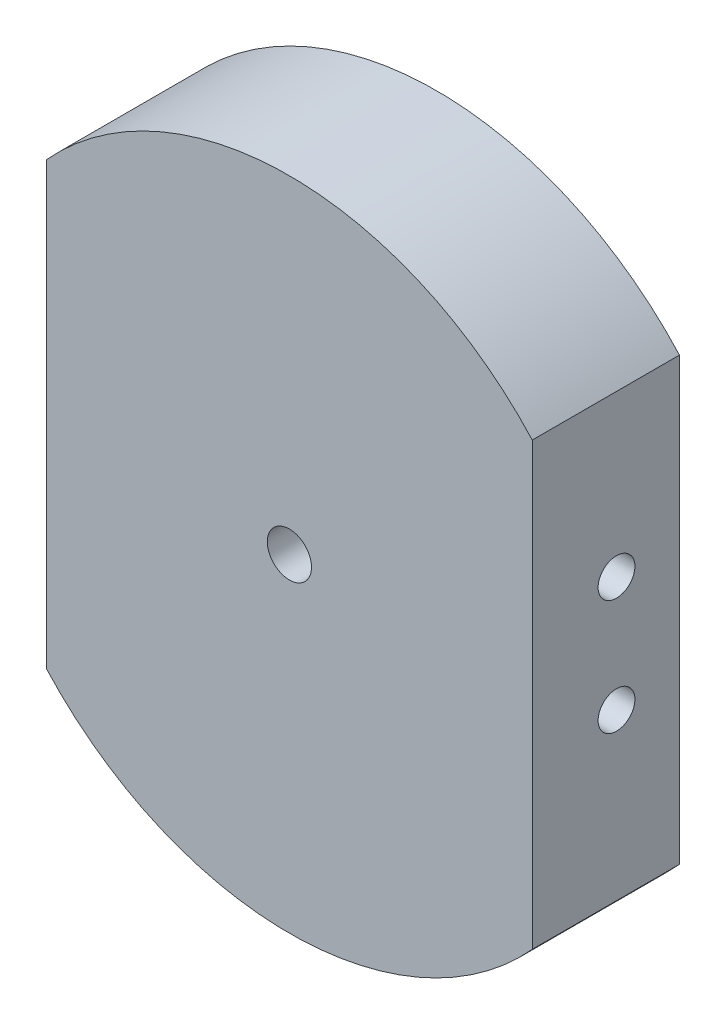
SolidWorks part; units mm, degrees
ref_plane "Front Plane" through (0, 0, 0) normal (0, 0, 1) x (1, 0, 0)
ref_plane "Top Plane" through (0, 0, 0) normal (0, 1, 0) x (1, 0, 0)
ref_plane "Right Plane" through (0, 0, 0) normal (1, 0, 0) x (0, 0, -1)
sketch "Sketch1" plane through (0, 0, 0) normal (0, 0, 1) x (1, 0, 0)
  circle A0 centre (0, 0) radius 55
  circle A1 centre (0, 0) radius 3
extrude "Boss-Extrude1" add sketch "Sketch1" along normal blind 20
sketch "Sketch2" plane through (0, 0, 20) normal (0, 0, 1) x (1, 0, 0)
  line L0 (-55, 0) -> (55, 0) construction
  line L1 (-54.0833, -10) -> (54.0833, -10) construction
  line L2 (-47.962, 14.4195) -> (-41.962, 14.4195) construction
  line L7 (-41.362, 16.6207) -> (-41.362, -16.6207)
  line L8 (0, 0) -> (0, 19.7694) construction
  line L9 (41.362, 16.6207) -> (41.362, -16.6207)
  line L11 (48.562, 0) -> (48.562, -1.9737)
  circle A0 centre (0, 0) radius 55 construction
  circle A1 centre (0, 0) radius 52
  arc A2 (-41.362, -16.6207) -> (41.362, -16.6207) centre (0, 0) ccw
  arc A7 (-41.362, 16.6207) -> (41.362, 16.6207) centre (0, 0) cw
  dimension "D3" = 10
extrude "Cut-Extrude1" cut sketch "Sketch2" against normal blind 10
sketch "Sketch3" plane through (0, 0, 20) normal (0, 0, 1) x (1, 0, 0)
  line L2 (-41.362, 16.6207) -> (-41.362, -16.6207)
  line L3 (41.362, -16.6207) -> (41.362, 16.6207)
  line L4 (-41.362, 16.6207) -> (-41.362, -16.6207)
  line L5 (41.362, -16.6207) -> (41.362, 16.6207)
  circle A0 centre (0, 0) radius 73.6451
  arc A2 (41.362, 16.6207) -> (-41.362, 16.6207) centre (0, 0) ccw
  arc A3 (-41.362, -16.6207) -> (41.362, -16.6207) centre (0, 0) ccw
  arc A4 (41.362, 16.6207) -> (-41.362, 16.6207) centre (0, 0) ccw
  arc A5 (-41.362, -16.6207) -> (41.362, -16.6207) centre (0, 0) ccw
  dimension "D1" = 0
extrude "Cut-Extrude2" cut sketch "Sketch3" against normal blind 40
sketch "Sketch6" plane through (0, 0, 0) normal (0, 0, -1) x (-1, 0, 0)
  line L0 (0, 44.5764) -> (0, -44.5764) construction
  line L1 (33, 29.9676) -> (59.4435, 26.8152)
  line L2 (-33, 29.9676) -> (33, 29.9676)
  line L3 (-33, 29.9676) -> (-33, -29.9676)
  line L4 (-33, -29.9676) -> (33, -29.9676)
  line L5 (33, 29.9676) -> (33, -29.9676)
  line L6 (-33, 29.9676) -> (33, -29.9676) construction
  line L7 (-33, -29.9676) -> (33, 29.9676) construction
  line L8 (59.4435, 26.8152) -> (59.4435, -14.2915)
  line L9 (59.4435, -14.2915) -> (33, -29.9676)
  line L10 (-33, 29.9676) -> (-58.6751, 18.0052)
  line L11 (-58.6751, 18.0052) -> (-58.6751, -19.3878)
  line L12 (-58.6751, -19.3878) -> (-33, -29.9676)
  arc A0 (41.362, 16.6207) -> (-41.362, 16.6207) centre (0, 0) ccw construction
  arc A1 (-41.362, -16.6207) -> (41.362, -16.6207) centre (0, 0) ccw construction
  point P8 (0, 0)
  arc M6 (41.362, 16.6207) -> (-41.362, 16.6207) centre (0, 0) ccw
  line M7 (-41.362, 16.6207) -> (-41.362, -16.6207)
  arc M8 (-41.362, -16.6207) -> (41.362, -16.6207) centre (0, 0) ccw
  line M9 (41.362, -16.6207) -> (41.362, 16.6207)
  dimension "D1" = 66
extrude "Cut-Extrude4" cut sketch "Sketch6" against normal blind 58 contours L11 L12 L10 M8 M7 M6 | L3 M6 M7 M8 | L9 L8 L1 M6 M9 M8 | L5 M6 M8 M9
sketch "Sketch5" plane through (33, 0, 0) normal (1, 0, 0) x (0, 0, -1)
  line L0 (-40.5358, 0.6222) -> (19.4642, 0.6222) construction
  line L1 (-20, -29.9676) -> (-20, 29.9676) construction
  circle A0 centre (-8.5533, -7.5178) radius 2.5
  circle A1 centre (-8.5533, 8.14) radius 2.5
  point P6 (0, 0)
  point P10 (0, 0)
  dimension "D1" = 8.14
  dimension "D2" = 5
  dimension "D3" = 11.4467
extrude "Cut-Extrude3" cut sketch "Sketch5" against normal blind 110
